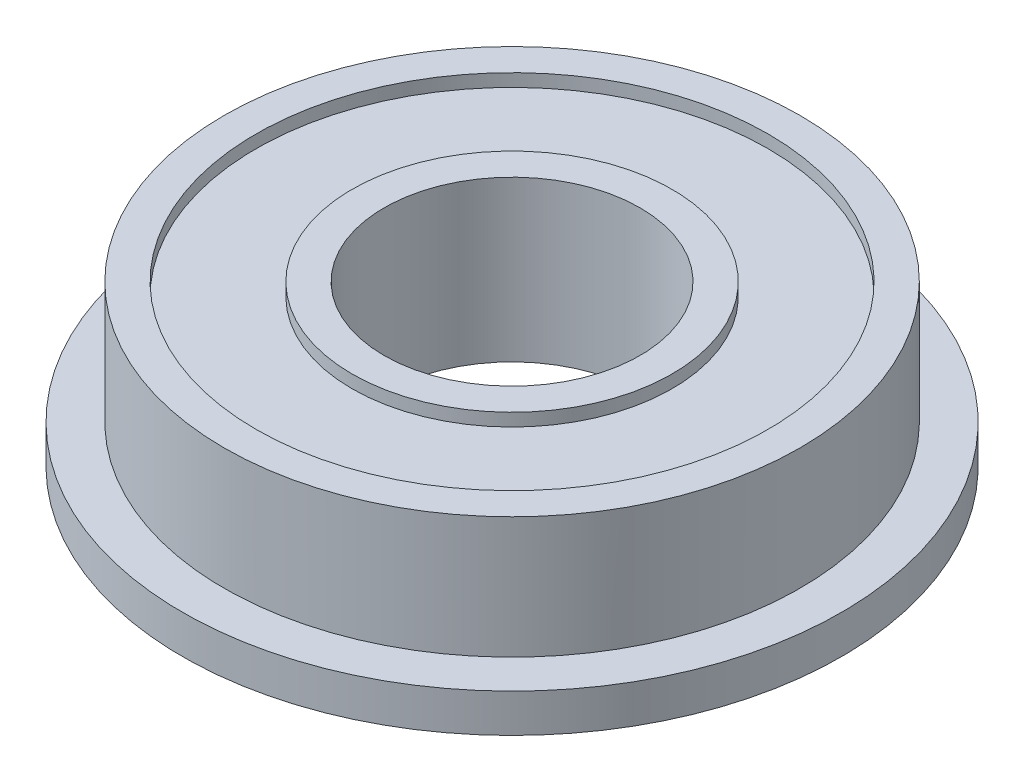
SolidWorks part; units mm, degrees
material "6061 合金"
ref_plane "Front Plane" through (0, 0, 0) normal (0, 0, 1) x (1, 0, 0)
ref_plane "Top Plane" through (0, 0, 0) normal (0, 1, 0) x (1, 0, 0)
ref_plane "Right Plane" through (0, 0, 0) normal (1, 0, 0) x (0, 0, -1)
other "Configuration Table"
sketch "草图1" plane through (0, 0, 0) normal (0, 1, 0) x (1, 0, 0)
  circle A0 centre (0, 0) radius 4.5
  circle A1 centre (0, 0) radius 2
  dimension "D1" = 9
  dimension "D2" = 4
extrude "凸台-拉伸1" add sketch "草图1" along normal blind 2.5
sketch "草图2" plane through (0, 0, 0) normal (0, -1, 0) x (1, 0, 0)
  circle A0 centre (0, 0) radius 5.15
  circle A1 centre (0, 0) radius 2 construction
  circle A2 centre (0, 0) radius 2
  dimension "D1" = 10.3
extrude "凸台-拉伸2" add sketch "草图2" against normal blind 0.6
sketch "草图4" plane through (0, 2.5, 0) normal (0, 1, 0) x (1, 0, 0)
  circle A0 centre (0, 0) radius 2.5
  circle A1 centre (0, 0) radius 4
  circle A2 centre (0, 0) radius 4.5 construction
  circle A3 centre (0, 0) radius 2 construction
  dimension "D1" = 0.5
  dimension "D2" = 0.5
extrude "切除-拉伸1" cut sketch "草图4" against normal blind 0.2
ref_plane "基准面1" through (0, 1.25, 0) normal (0, -1, 0) x (-1, 0, 0)
mirror "镜向1" about plane through (0, 1.25, 0) normal (0, -1, 0) of "切除-拉伸1"
